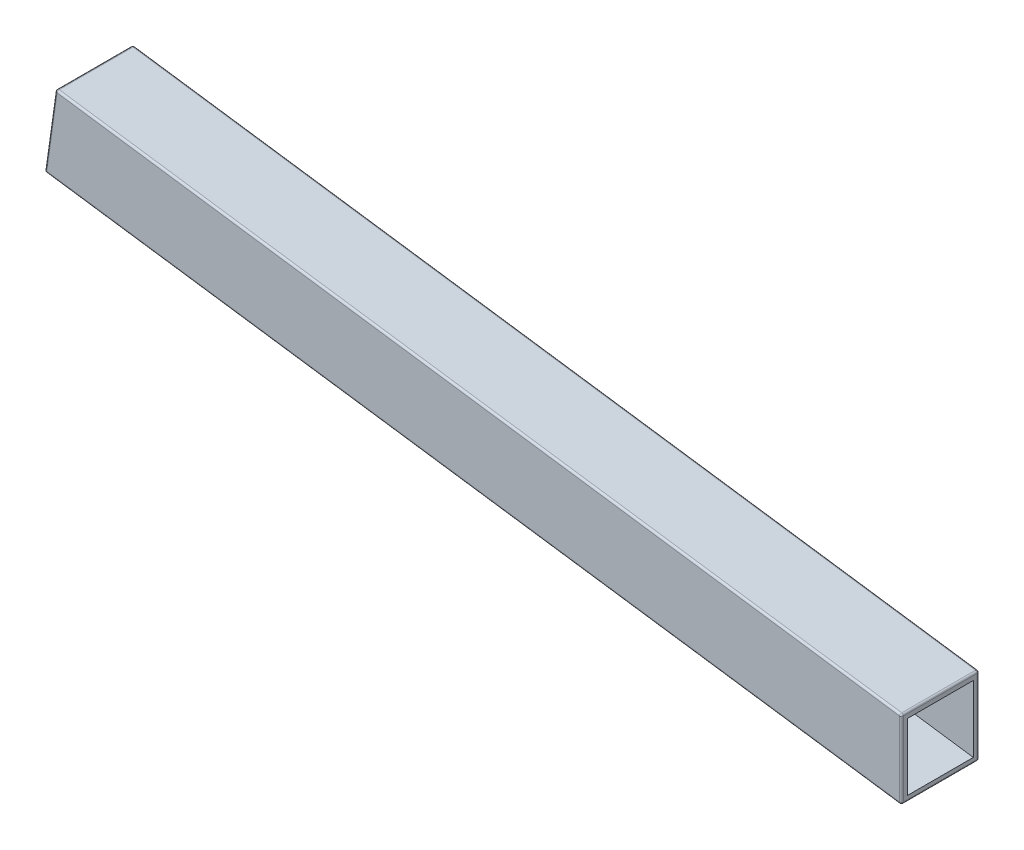
SolidWorks part; units mm, degrees
ref_plane "Front Plane" through (0, 0, 0) normal (0, 0, 1) x (1, 0, 0)
ref_plane "Top Plane" through (0, 0, 0) normal (0, 1, 0) x (1, 0, 0)
ref_plane "Right Plane" through (0, 0, 0) normal (1, 0, 0) x (0, 0, -1)
sketch "Sketch1" plane through (0, 0, 0) normal (0, 0, 1) x (1, 0, 0)
  line L0 (119.9742, 0) -> (-143.6311, 0) construction
  line L1 (0, 0) -> (-441.2849, 62.0185)
  line L2 (-441.2849, 62.0185) -> (-435.718, 101.6293)
  line L3 (-435.718, 101.6293) -> (0, 40.3931)
  line L4 (0, 40.3931) -> (0, 0)
  dimension "D1" = 8
  dimension "D2" = 40
  dimension "D3" = 440
extrude "Boss-Extrude1" add sketch "Sketch1" along normal blind 40
sketch "Sketch2" plane through (-441.2849, 62.0185, 0) normal (-0.9903, 0.1392, 0) x (0, 0, 1)
  line L0 (3, 37) -> (37, 37)
  line L1 (37, 37) -> (37, 3)
  line L2 (37, 3) -> (3, 3)
  line L3 (3, 3) -> (3, 37)
  line L4 (40, 40) -> (0, 40) construction
  line L5 (0, 40) -> (0, 0) construction
  line L6 (40, 40) -> (40, 0) construction
  line L7 (40, 0) -> (0, 0) construction
  dimension "D1" = 3
  dimension "D2" = 3
  dimension "D3" = 3
  dimension "D4" = 3
extrude "Cut-Extrude1" cut sketch "Sketch2" against normal through all
fillet "Fillet1" radius 1 12 edges at (-441.2849, 62.0185, 20) (0, 0, 20) (-438.5014, 81.8239, 0) (-220.6424, 31.0093, 0) (0, 20.1966, 0) (0, 40.3931, 20) (-435.718, 101.6293, 20) (-217.859, 71.0112, 0) (-220.6424, 31.0093, 40) (-438.5014, 81.8239, 40) (-217.859, 71.0112, 40) (0, 20.1966, 40)
